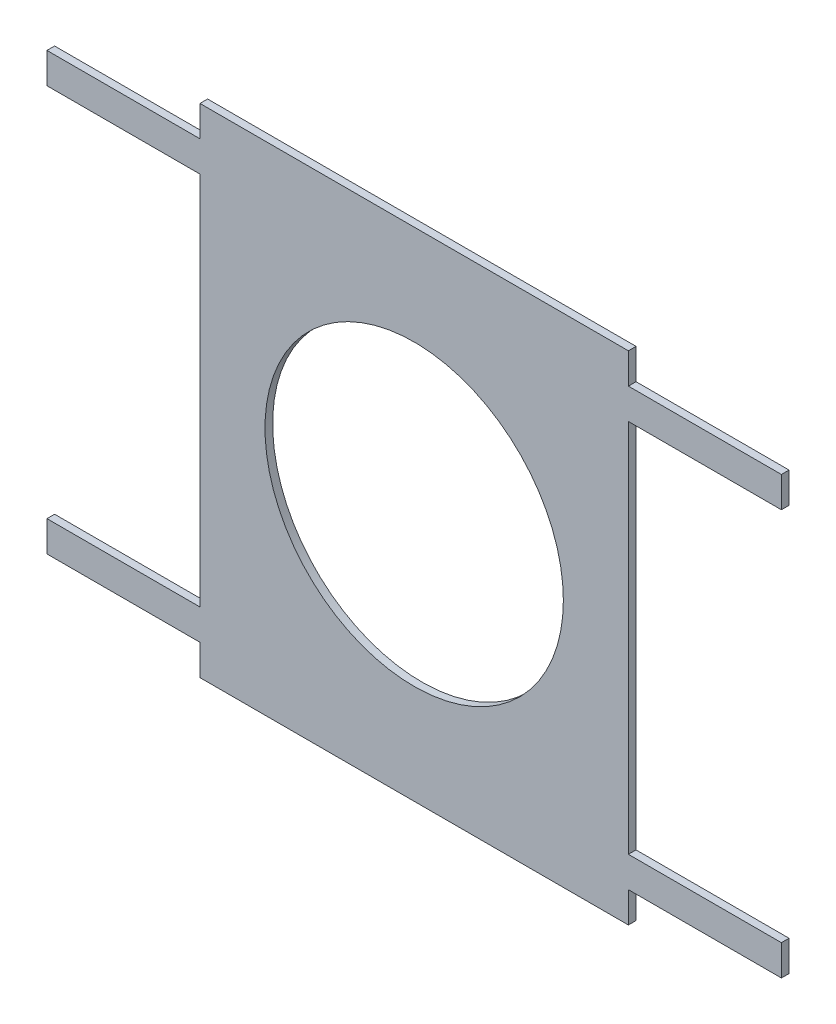
SolidWorks part; units mm, degrees
ref_plane "Front Plane" through (0, 0, 0) normal (0, 0, 1) x (1, 0, 0)
ref_plane "Top Plane" through (0, 0, 0) normal (0, 1, 0) x (1, 0, 0)
ref_plane "Right Plane" through (0, 0, 0) normal (1, 0, 0) x (0, 0, -1)
sketch "Sketch1" plane through (0, 0, 0) normal (0, 0, 1) x (1, 0, 0)
  line L0 (0, -55) -> (0, 55) construction
  line L1 (-1.4, -1.625) -> (1.4, -1.625)
  line L2 (-1.4, -1.625) -> (-1.4, 1.625)
  line L3 (-1.4, 1.625) -> (1.4, 1.625)
  line L4 (1.4, -1.625) -> (1.4, 1.625)
  line L5 (-1.4, -1.625) -> (1.4, 1.625) construction
  line L6 (-1.4, 1.625) -> (1.4, -1.625) construction
  line L7 (-1.4, -1.425) -> (-2.4, -1.425)
  line L8 (-1.4, -1.425) -> (-1.4, -1.225)
  line L9 (-1.4, -1.225) -> (-2.4, -1.225)
  line L10 (-2.4, -1.425) -> (-2.4, -1.225)
  line L15 (1.4, -1.225) -> (2.4, -1.225)
  line L16 (2.4, -1.425) -> (2.4, -1.225)
  line L17 (1.4, -1.425) -> (2.4, -1.425)
  line L18 (1.4, -1.425) -> (1.4, -1.225)
  line L19 (55, 0) -> (-55, 0) construction
  line L20 (1.4, 1.425) -> (1.4, 1.225)
  line L21 (1.4, 1.425) -> (2.4, 1.425)
  line L22 (2.4, 1.425) -> (2.4, 1.225)
  line L23 (1.4, 1.225) -> (2.4, 1.225)
  line L24 (-1.4, 1.225) -> (-2.4, 1.225)
  line L25 (-2.4, 1.425) -> (-2.4, 1.225)
  line L26 (-1.4, 1.425) -> (-2.4, 1.425)
  line L27 (-1.4, 1.425) -> (-1.4, 1.225)
  circle A0 centre (0, 0) radius 0.975
  point P0 (0, 0)
  dimension "D6" = 1.95
  dimension "D1" = 2.45
  dimension "D2" = 2.8
  dimension "D3" = 0.2
  dimension "D4" = 1
  dimension "D5" = 0.2
extrude "Boss-Extrude1" add sketch "Sketch1" along normal blind 0.05 contours L1 L4 L3 L2 | L10 L7 L2 L9 | L4 L17 L16 L15 | L4 L23 L22 L21 | L2 L26 L25 L24
